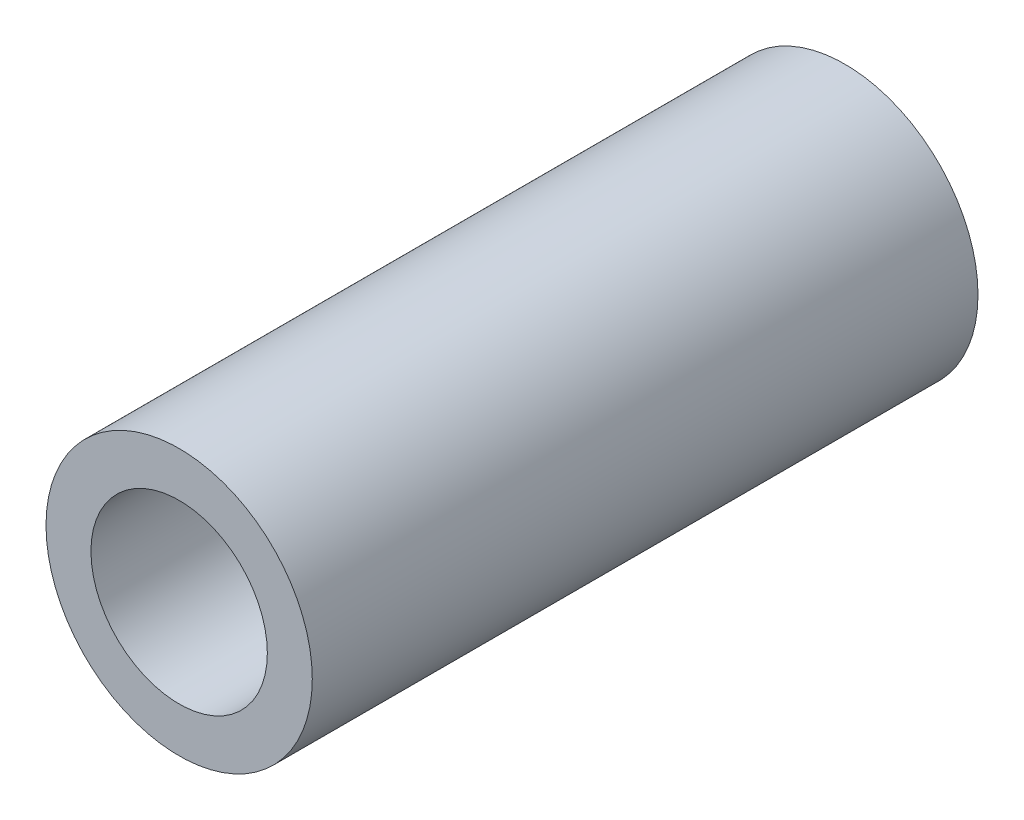
SolidWorks part; units mm, degrees
ref_plane "Front Plane" through (0, 0, 0) normal (0, 0, 1) x (1, 0, 0)
ref_plane "Top Plane" through (0, 0, 0) normal (0, 1, 0) x (1, 0, 0)
ref_plane "Right Plane" through (0, 0, 0) normal (1, 0, 0) x (0, 0, -1)
sketch "Sketch1" plane through (0, 0, 0) normal (0, 0, 1) x (1, 0, 0)
  circle A0 centre (0, 0) radius 4
  circle A1 centre (0, 0) radius 2.65
  dimension "OD" = 8
  dimension "ID" = 5.3
extrude "Extrude1" add sketch "Sketch1" along normal mid plane 20
sketch "Sketch2" plane through (0, 0, 0) normal (1, 0, 0) x (0, 0, -1)
  line L0 (-10, -2.65) -> (10, -2.65) construction
  line L3 (10, 2.65) -> (-10, 2.65) construction
  line L5 (-10, -2.65) -> (10, -2.65)
  line L6 (10, 2.65) -> (-10, 2.65)
sketch "Sketch4" plane through (0, 0, 10) normal (0, 0, 1) x (1, 0, 0)
  line L0 (0, 0) -> (-1.8738, 1.8738)
  line L1 (0, -4.4) -> (0, 4.4) construction
  circle A0 centre (0, 0) radius 2.65 construction
  dimension "D1" = 45
